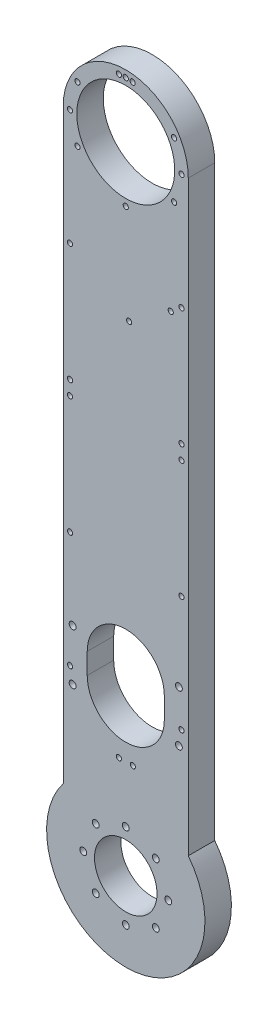
SolidWorks part; units mm, degrees
material "6061 Alloy"
ref_plane "Front" through (0, 0, 0) normal (0, 0, 1) x (1, 0, 0)
ref_plane "Top" through (0, 0, 0) normal (0, 1, 0) x (1, 0, 0)
ref_plane "Right" through (0, 0, 0) normal (1, 0, 0) x (0, 0, -1)
ref_plane "Plane1" through (0, 0, 12.7) normal (0, 0, 1) x (1, 0, 0)
sketch "Sketch1" plane through (0, 0, 12.7) normal (0, 0, 1) x (1, 0, 0)
  line L0 (30, 23.3238) -> (30, 305)
  line L1 (-30, 305) -> (-30, 23.3238)
  line L2 (18.5, 84.0225) -> (18.5, 74.0225)
  line L3 (-18.5, 74.0225) -> (-18.5, 84.0225)
  arc A0 (-30, 23.3238) -> (30, 23.3238) centre (0, 0) ccw
  arc A1 (30, 305) -> (-30, 305) centre (0, 305) ccw
  arc A2 (-18.5, 84.0225) -> (18.5, 84.0225) centre (0, 84.0225) cw
  arc A3 (18.5, 74.0225) -> (-18.5, 74.0225) centre (0, 74.0225) cw
  circle A4 centre (0, 0) radius 15
  circle A5 centre (0, 305) radius 23.5
  dimension "D1" = 30
  dimension "D2" = 38
extrude "Boss-Extrude1" add sketch "Sketch1" against normal blind 12.7
hole_wizard "M3x0.5 Tapped Hole1" positions "Sketch2" profile "Sketch3" tap size "M3x0.5" standard "ANSI Metric" end condition up to next
sketch "Sketch2" plane through (0, 0, 12.7) normal (0, 0, 1) x (1, 0, 0)
  point P0 (0, 331.75)
  point P3 (3.3, 331.5457)
  point P6 (23.1662, 318.375)
  point P9 (26.75, 305)
  point P12 (23.1662, 291.625)
  point P15 (0, 278.25)
  point P18 (-23.1662, 291.625)
  point P21 (-26.75, 305)
  point P24 (-23.1662, 318.375)
  point P27 (-3.3, 331.5457)
  point P30 (26.75, 249.5112)
  point P33 (21.5789, 245.4337)
  point P36 (1.6199, 231.2653)
  point P39 (-26.75, 249.5112)
  point P42 (-26.75, 192.9112)
  point P45 (-26.75, 186.1112)
  point P48 (26.75, 192.9112)
  point P51 (26.75, 186.1112)
  point P54 (-26.75, 129.5112)
  point P57 (26.75, 129.5112)
  point P60 (-26.75, 74.0225)
  point P63 (-3.3, 47.4768)
  point P66 (3.4, 47.4894)
  point P69 (26.75, 74.0225)
sketch "Sketch3" plane through (0, 331.75, 12.7) normal (1, 0, 0) x (0, -1, 0)
  line L0 (0, 0) -> (0, 12.7)
  line L1 (0, 12.7) -> (1.25, 12.7)
  line L2 (1.25, 12.7) -> (1.25, 0)
  line L5 (1.25, 0) -> (0, 0)
  line L11 (0, -6.35) -> (0, 107.95) construction
  dimension "Thru Tap Drill Dia." = 2.5
  dimension "Thru Tap Drill Depth" = 12.7
hole_wizard "M4x0.7 Tapped Hole1" positions "3DSketch1" profile "Sketch4" tap size "M4x0.7" standard "ANSI Metric" end condition up to next
sketch3d "3DSketch1"
  point P0 (0, 20.4, 12.7)
  point P4 (14.425, 14.425, 12.7)
  point P8 (20.4, 0, 12.7)
  point P12 (14.425, -14.425, 12.7)
  point P16 (0, -20.4, 12.7)
  point P20 (-14.425, -14.425, 12.7)
  point P24 (-20.4, 0, 12.7)
  point P28 (-14.425, 14.425, 12.7)
  point P32 (25.5016, 66.7725, 12.7)
  point P36 (25.5016, 91.2725, 12.7)
  point P40 (-25.5016, 91.2725, 12.7)
  point P44 (-25.5016, 66.7725, 12.7)
sketch "Sketch4" plane through (0, 20.4, 12.7) normal (1, 0, 0) x (0, -1, 0)
  line L0 (0, 0) -> (0, 12.7)
  line L1 (0, 12.7) -> (1.65, 12.7)
  line L2 (1.65, 12.7) -> (1.65, 0)
  line L5 (1.65, 0) -> (0, 0)
  line L11 (0, -6.35) -> (0, 107.95) construction
  dimension "Thru Tap Drill Dia." = 3.3
  dimension "Thru Tap Drill Depth" = 12.7
